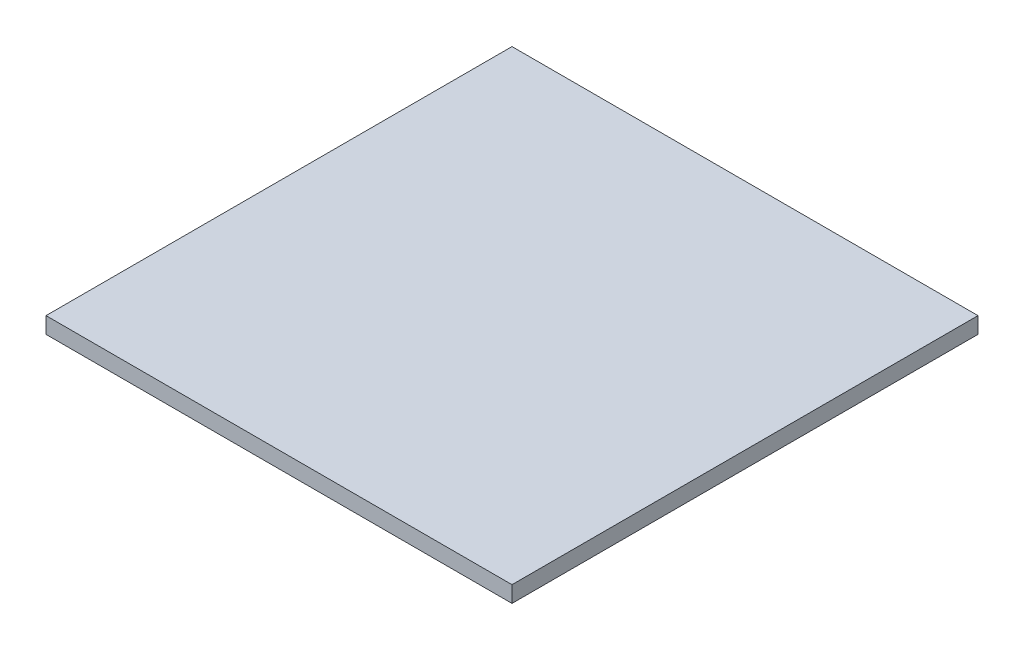
SolidWorks part; units mm, degrees
ref_plane "Front Plane" through (0, 0, 0) normal (0, 0, 1) x (1, 0, 0)
ref_plane "Top Plane" through (0, 0, 0) normal (0, 1, 0) x (1, 0, 0)
ref_plane "Right Plane" through (0, 0, 0) normal (1, 0, 0) x (0, 0, -1)
sketch "Sketch1" plane through (0, 0, 0) normal (0, 1, 0) x (1, 0, 0)
  line L1 (4300, -4300) -> (-4300, -4300)
  line L2 (4300, -4300) -> (4300, 4300)
  line L3 (4300, 4300) -> (-4300, 4300)
  line L4 (-4300, -4300) -> (-4300, 4300)
  line L5 (4300, -4300) -> (-4300, 4300) construction
  line L6 (4300, 4300) -> (-4300, -4300) construction
  point P0 (0, 0)
  dimension "D1" = 8600
  dimension "D2" = 8600
extrude "Boss-Extrude1" add sketch "Sketch1" along normal blind 300
